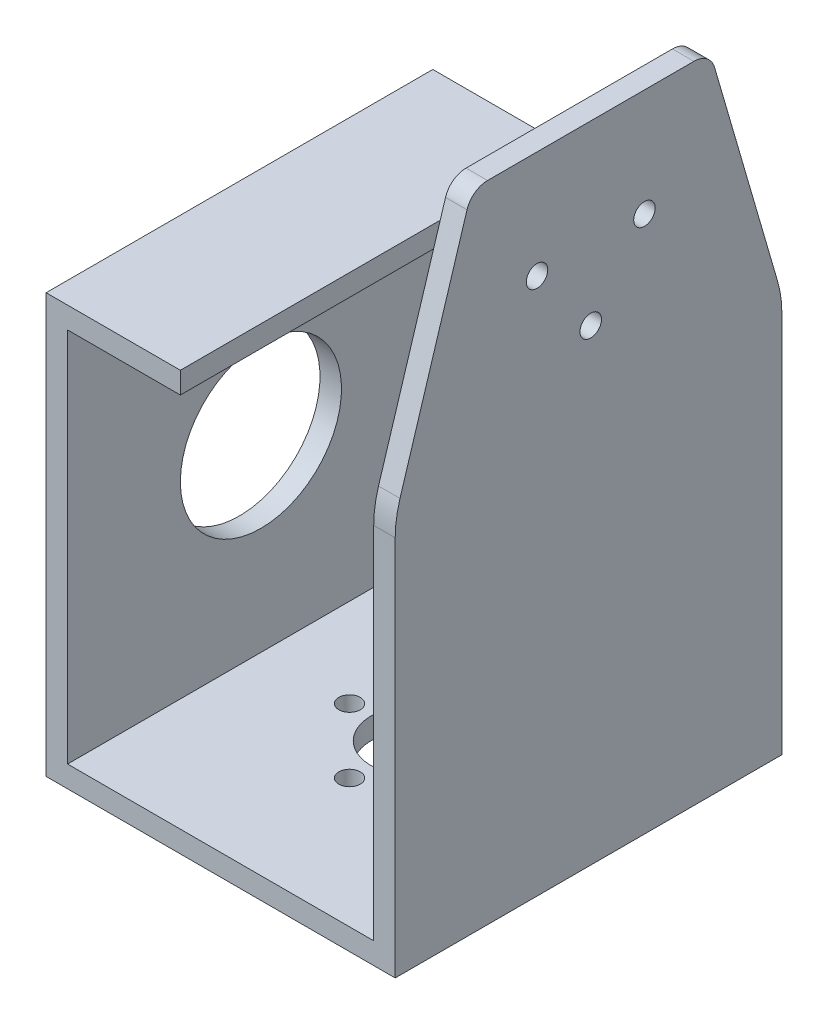
SolidWorks part; units mm, degrees
ref_plane "Front Plane" through (0, 0, 0) normal (0, 0, 1) x (1, 0, 0)
ref_plane "Top Plane" through (0, 0, 0) normal (0, 1, 0) x (1, 0, 0)
ref_plane "Right Plane" through (0, 0, 0) normal (1, 0, 0) x (0, 0, -1)
sketch "Sketch1" plane through (0, 0, 0) normal (0, 0, 1) x (1, 0, 0)
  line L0 (0, 0) -> (-10.5, 0)
  line L1 (-10.5, 0) -> (-10.5, -35)
  line L2 (-10.5, -35) -> (18, -35)
  line L3 (18, -35) -> (18, 23)
  line L4 (0, 2) -> (-12.5, 2)
  line L5 (-12.5, 2) -> (-12.5, -37)
  line L6 (-12.5, -37) -> (20, -37)
  line L7 (20, -37) -> (20, 23)
  line L8 (0, 2) -> (0, 0)
  line L9 (18, 23) -> (20, 23)
  dimension "D1" = 10.5
  dimension "D2" = 28.5
  dimension "D3" = 35
  dimension "D4" = 58
  dimension "D5" = 2
extrude "Boss-Extrude1" add sketch "Sketch1" along normal blind 36
sketch "Sketch2" plane through (20, 0, 0) normal (1, 0, 0) x (0, 0, -1)
  line L0 (-27.4035, 23) -> (-8.1917, 23)
  line L1 (-35.5525, 1.4452) -> (-29.314, 21.5916)
  line L2 (-36, 23) -> (0, 23) construction
  line L3 (-0.398, 1.3682) -> (-6.2713, 21.5586)
  line L4 (-36, -1.5129) -> (-36, -37)
  line L5 (-36, -37) -> (0, -37)
  line L6 (0, -37) -> (0, -1.425)
  line L7 (-22.7976, 13) -> (-12.7976, 13) construction
  arc A0 (0, -1.425) -> (-0.398, 1.3682) centre (-10, -1.425) ccw
  arc A1 (-35.5525, 1.4452) -> (-36, -1.5129) centre (-26, -1.5129) ccw
  arc A2 (-6.2713, 21.5586) -> (-8.1917, 23) centre (-8.1917, 21) ccw
  arc A3 (-29.314, 21.5916) -> (-27.4035, 23) centre (-27.4035, 21) cw
  circle A4 centre (-17.7976, 6.5) radius 1
  circle A5 centre (-22.7976, 13) radius 1
  circle A6 centre (-12.7976, 13) radius 1
  point P14 (0, 0)
  point P17 (-36, 0)
  point P20 (-6.6906, 23)
  point P23 (-28.8779, 23)
  point P30 (-17.7976, 23)
  point P31 (-17.7976, 13)
  dimension "D1" = 10
  dimension "D2" = 2
  dimension "D3" = 2
  dimension "D4" = 10
  dimension "D5" = 6.5
  dimension "D6" = 5
extrude "Cut-Extrude2" cut sketch "Sketch2" against normal blind 5 flip side to cut
sketch "Sketch3" plane through (-12.5, 0, 0) normal (-1, 0, 0) x (0, 0, 1)
  circle A0 centre (18, -17.5) radius 7.5
  dimension "D1" = 15
extrude "Cut-Extrude3" cut sketch "Sketch3" against normal blind 5
sketch "Sketch4" plane through (0, -37, 0) normal (0, -1, 0) x (1, 0, 0)
  circle A0 centre (3.75, 18) radius 4
  circle A1 centre (9.75, 18) radius 1
  circle A2 centre (3.75, 12) radius 1
  circle A3 centre (3.75, 18) radius 4
  circle A4 centre (-2.25, 18) radius 1
  circle A5 centre (3.75, 18) radius 4
  circle A6 centre (3.75, 24) radius 1
  circle A7 centre (3.75, 18) radius 4
  point P16 (3.75, 18)
  dimension "D1" = 8
  dimension "D2" = 2
  dimension "D4" = 6
  dimension "D3" = 4
extrude "Cut-Extrude5" cut sketch "Sketch4" against normal blind 5 contours A0 | A2 | A6 | A1 | A4
